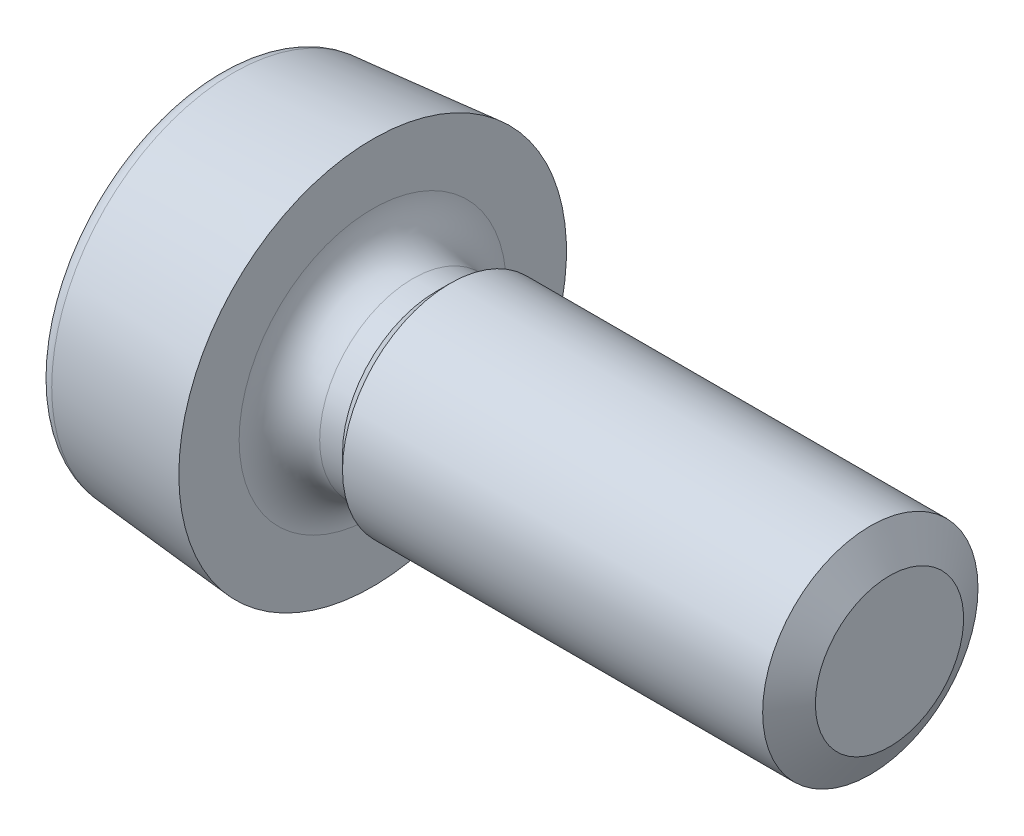
SolidWorks part; units mm, degrees
revolve "基体-旋转" add sketch "草图3" angle 360 about L0
sketch "草图3" plane through (0, 0, 0) normal (0, 0, 1) x (1, 0, 0)
  line L0 (-2.1696, 0) -> (16.014, 0) construction
  line L1 (0, 0) -> (7.8, 0)
  line L2 (7.8, 0) -> (7.8, 1.25)
  line L3 (7.8, 1.25) -> (2.7, 1.25)
  line L4 (2.7, 1.25) -> (2.5325, 1.0825)
  line L5 (2.5325, 1.0825) -> (2.2675, 1.0825)
  line L7 (1.8, 2.25) -> (0.1826, 2.1085)
  line L8 (0, 1.9093) -> (0, 0)
  line L9 (1.8, 1.55) -> (1.8, 2.25)
  arc A0 (1.8, 1.55) -> (2.2675, 1.0825) centre (2.2675, 1.55) ccw
  arc A1 (0.1826, 2.1085) -> (0, 1.9093) centre (0.2, 1.9093) ccw
  dimension "D4" = 0.2
  dimension "D1" = 5
  dimension "dk" = 4.5
  dimension "d" = 2.5
  dimension "D2" = 45
  dimension "da" = 3.1
  dimension "k" = 1.8
  dimension "D3" = 2.165
  dimension "a" = 0.9
  dimension "l" = 6
cosmetic thread "装饰螺纹线1" parameters "D2"=2.165
material "AISI 304"
ref_plane "前视" through (0, 0, 0) normal (0, 0, 1) x (1, 0, 0)
ref_plane "上视" through (0, 0, 0) normal (0, 1, 0) x (1, 0, 0)
ref_plane "右视" through (0, 0, 0) normal (1, 0, 0) x (0, 0, -1)
sketch "尺寸草图" plane through (0, 0, 0) normal (0, 0, 1) x (1, 0, 0)
  line L0 (0, 0) -> (6, 0)
  line L1 (0, 0) -> (0, 4.5)
  line L2 (6, 0) -> (6, 2.5)
  point P5 (0, 3.1)
  point P6 (1.8, 0)
  point P7 (2.7, 0)
  point P8 (5.55, 0)
  point P9 (4.8, 0)
  point P10 (3.3, 0)
  point P11 (0, 0.1)
  dimension "dk" = 4.5
  dimension "d" = 2.5
  dimension "da" = 3.1
  dimension "k" = 1.8
  dimension "a" = 0.9
  dimension "l" = 6
  dimension "P" = 0.45
  dimension "h" = 1.2
  dimension "m" = 2.7
  dimension "r" = 0.1
sketch "草图4" plane through (0, 0, 0) normal (0, 0, 1) x (1, 0, 0)
  line L0 (7.5774, 1.25) -> (8.0274, 1.25)
  line L1 (8.0274, 1.25) -> (7.8, 0.8603)
  line L2 (7.8, 0.8603) -> (7.5774, 1.25)
  line L3 (7.8, 1.25) -> (2.7, 1.25) construction
  line L4 (7.8, -1.25) -> (7.8, 1.25) construction
  line L5 (-0.218, 0) -> (14.7427, 0) construction
  line L6 (-2.1696, 0) -> (16.014, 0) construction
  dimension "D1" = 0.45
  dimension "D2" = 0.3897
  dimension "D3" = 60
revolve "切除-旋转1" cut sketch "草图4" angle 360 about L5
pattern_linear "阵列(线性)1" [suppressed] count 11 spacing 0.45 along (1, 0, 0)
sketch "草图5" plane through (0, 0, 0) normal (-1, 0, 0) x (0, 0, 1)
  line L1 (-0.225, 1.35) -> (0.225, 1.35)
  line L2 (-0.225, 1.35) -> (-0.225, -1.35)
  line L3 (-0.225, -1.35) -> (0.225, -1.35)
  line L4 (0.225, 1.35) -> (0.225, -1.35)
  point P4 (-0.225, 0)
  point P5 (0, 1.35)
  dimension "m" = 2.7
  dimension "D1" = 0.45
ref_plane "基准面1" through (1.2, 0, 0) normal (1, 0, 0) x (0, 0, -1)
sketch "草图6" plane through (1.2, 0, 0) normal (1, 0, 0) x (0, 0, -1)
  point P0 (0, 0)
loft "切除-放样1" cut profiles "草图5", "草图6"
pattern_circular "阵列(圆周)1" count 2 every 90 about axis through (0, 0, 0) along (1, 0, 0) of "切除-放样1"
equation "\"l@草图3\" = \"l@尺寸草图\""
equation "\"dk@草图3\" = \"dk@尺寸草图\""
equation "\"da@草图3\" = \"da@尺寸草图\""
equation "\"D4@草图3\" = \"r@尺寸草图\"*2"
equation "\"k@草图3\" = \"k@尺寸草图\""
equation "\"a@草图3\" = \"a@尺寸草图\""
equation "\"D3@草图3\" = \"d@尺寸草图\"*0.866"
equation "\"d@草图3\" = \"d@尺寸草图\""
equation "\"D2@装饰螺纹线1\" = \"d@尺寸草图\"*0.866"
equation "\"D1@草图4\" = \"P@尺寸草图\""
equation "\"D2@草图4\" = \"P@尺寸草图\"*0.866"
equation "\"D3@阵列(线性)1\" = \"P@尺寸草图\""
equation "\"D1@阵列(线性)1\" = (\"l@尺寸草图\"-\"a@尺寸草图\")/\"P@尺寸草图\""
equation "\"D1@基准面1\" = \"h@尺寸草图\""
equation "\"m@草图5\" = \"m@尺寸草图\""
equation "\"D1@草图5\" = \"P@尺寸草图\""
